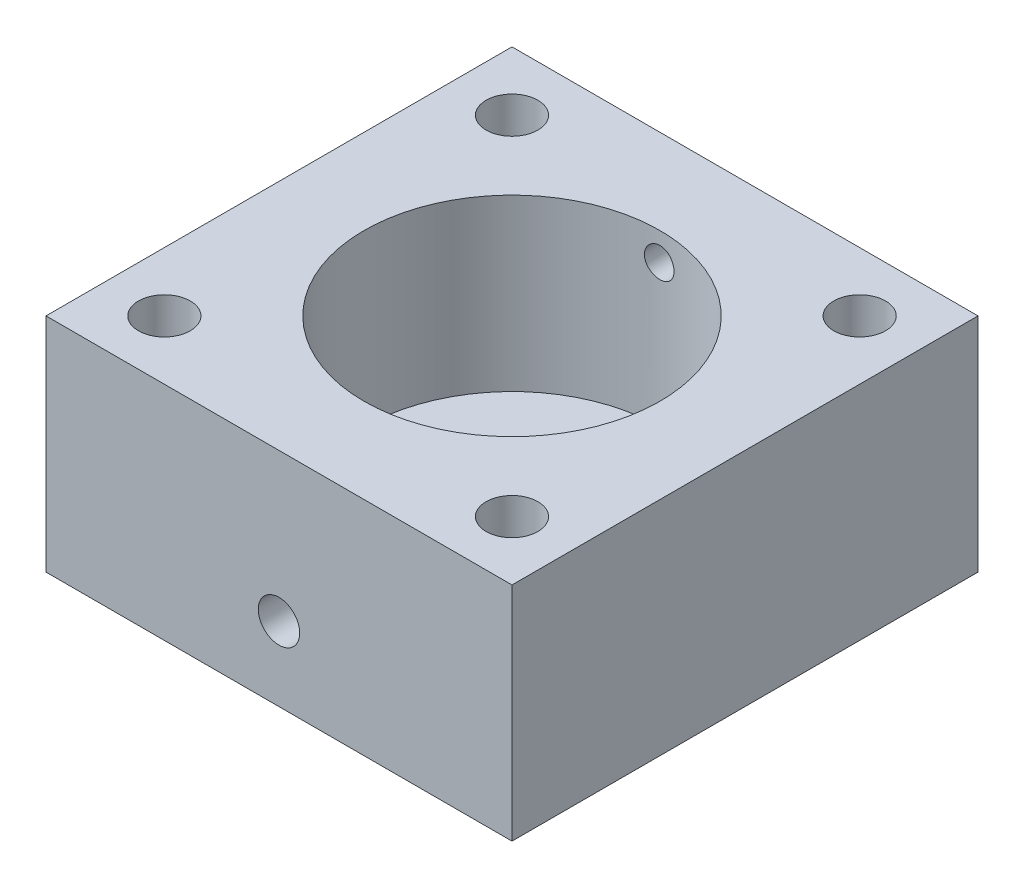
SolidWorks part; units mm, degrees
ref_plane "Alzado" through (0, 0, 0) normal (0, 0, 1) x (1, 0, 0)
ref_plane "Planta" through (0, 0, 0) normal (0, 1, 0) x (1, 0, 0)
ref_plane "Vista lateral" through (0, 0, 0) normal (1, 0, 0) x (0, 0, -1)
sketch "Croquis1" plane through (0, 0, 0) normal (0, 1, 0) x (1, 0, 0)
  line L1 (-15.75, -15.75) -> (15.75, -15.75)
  line L2 (-15.75, -15.75) -> (-15.75, 15.75)
  line L3 (-15.75, 15.75) -> (15.75, 15.75)
  line L4 (15.75, -15.75) -> (15.75, 15.75)
  line L5 (-15.75, -15.75) -> (15.75, 15.75) construction
  line L6 (-15.75, 15.75) -> (15.75, -15.75) construction
  point P0 (0, 0)
  dimension "D1" = 31.5
  dimension "D2" = 31.5
extrude "Saliente-Extruir1" add sketch "Croquis1" along normal blind 15 contours L3 L4 L1 L2
sketch "Croquis3" plane through (0, 15, 0) normal (0, 1, 0) x (1, 0, 0)
  circle A0 centre (0, 0) radius 10
  dimension "D2" = 20
extrude "Cortar-Extruir1" cut sketch "Croquis3" against normal blind 11.5
sketch "Croquis6" plane through (0, 15, 0) normal (0, 1, 0) x (1, 0, 0)
  line L0 (-15.75, -15.75) -> (15.75, -15.75) construction
  line L1 (-15.75, -15.75) -> (-15.75, 15.75) construction
  line L2 (0, -15.75) -> (0, 15.75) construction
  line L3 (-15.75, 15.75) -> (15.75, 15.75) construction
  line L4 (-15.75, 0) -> (15.75, 0) construction
  line L5 (15.75, -15.75) -> (15.75, 15.75) construction
  circle A0 centre (-11.75, -11.75) radius 1.75
  circle A1 centre (11.75, -11.75) radius 1.75
  circle A2 centre (11.75, 11.75) radius 1.75
  circle A3 centre (-11.75, 11.75) radius 1.75
  dimension "D1" = 3.5
  dimension "D2" = 4
  dimension "D3" = 4
extrude "Cortar-Extruir2" cut sketch "Croquis6" against normal through all
sketch "Croquis7" plane through (0, 0, 15.75) normal (0, 0, 1) x (1, 0, 0)
  line L0 (-15.75, 0) -> (15.75, 0) construction
  circle A0 centre (0, 5) radius 1
  dimension "D1" = 5
  dimension "D2" = 2
extrude "Cortar-Extruir3" cut sketch "Croquis7" against normal up to surface (5.8001 mm away) contours A0
sketch "Croquis8" plane through (0, 0, -15.75) normal (0, 0, -1) x (-1, 0, 0)
  line L0 (0, 15) -> (0, 0) construction
  line L1 (15.75, 15) -> (-15.75, 15) construction
  circle A0 centre (0, 13.1237) radius 1
  circle A1 centre (0, 5) radius 1 construction
extrude "Cortar-Extruir4" cut sketch "Croquis8" against normal up to surface (5.8001 mm away) contours A0
sketch "Croquis9" plane through (0, 0, 15.75) normal (0, 0, 1) x (1, 0, 0)
  circle A0 centre (0, 5) radius 1.4
extrude "Cortar-Extruir5" cut sketch "Croquis9" against normal blind 2.5
sketch "Croquis10" plane through (0, 0, -15.75) normal (0, 0, -1) x (-1, 0, 0)
  circle A0 centre (0, 13.1237) radius 1.4
extrude "Cortar-Extruir6" cut sketch "Croquis10" against normal blind 2.5
